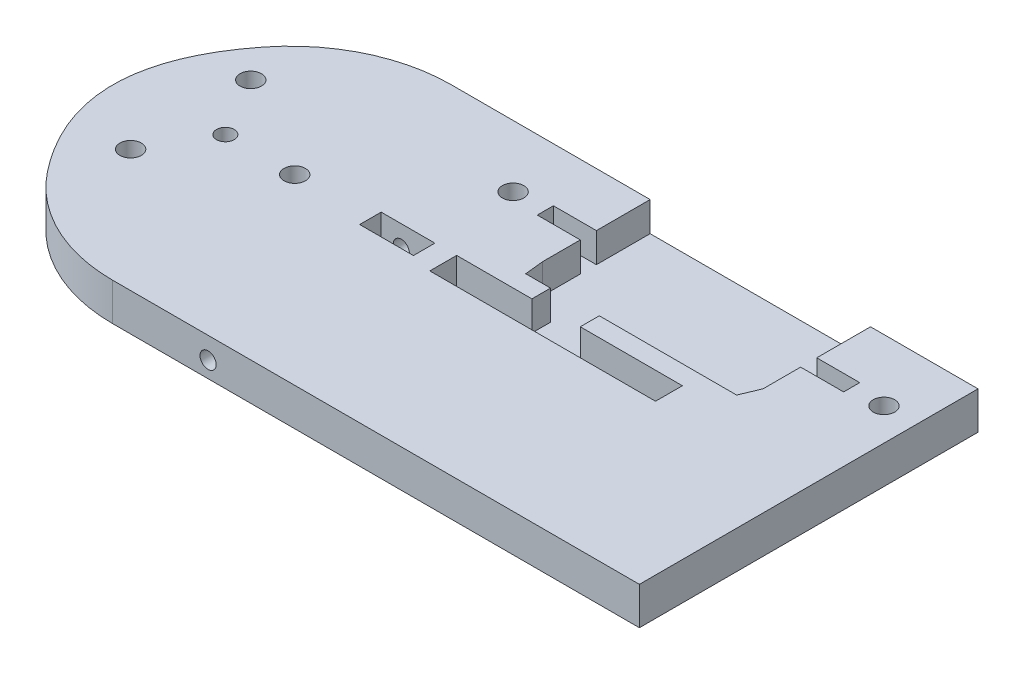
SolidWorks part; units mm, degrees
ref_plane "Plan de face" through (0, 0, 0) normal (0, 0, 1) x (1, 0, 0)
ref_plane "Plan de dessus" through (0, 0, 0) normal (0, 1, 0) x (1, 0, 0)
ref_plane "Plan de droite" through (0, 0, 0) normal (1, 0, 0) x (0, 0, -1)
sketch "Esquisse1" plane through (0, 0, 0) normal (0, 1, 0) x (1, 0, 0)
  line L0 (110, 31.5) -> (-33.3405, 31.5) construction
  line L1 (0, 0) -> (110, 0)
  line L3 (0, 63) -> (110, 63)
  line L4 (110, 0) -> (110, 63)
  spline S0 degree 2 poles (0, 63) (-38.9544, 31.5) (0, 0) knots 0 0 0 1 1 1
  dimension "D1" = 110
  dimension "D2" = 63
extrude "Boss.-Extru.1" add sketch "Esquisse1" along normal blind 7 contours S0 L1 L4 L3
sketch "Esquisse2" plane through (0, 7, 0) normal (0, 1, 0) x (1, 0, 0)
  line L0 (90, 63) -> (90, 53)
  line L1 (0, 63) -> (110, 63) construction
  line L2 (90, 53) -> (98, 53)
  line L3 (98, 53) -> (98, 50)
  line L4 (98, 50) -> (90, 50)
  line L5 (90, 50) -> (90, 43)
  line L6 (88.5483, 39.5408) -> (90, 43)
  line L7 (49, 43) -> (49, 50)
  line L8 (49, 50) -> (41, 50)
  line L9 (41, 50) -> (41, 53)
  line L10 (41, 53) -> (49, 53)
  line L11 (49, 53) -> (49, 63)
  line L12 (49, 63) -> (90, 63)
  line L13 (49, 43) -> (49.3831, 39.4665)
  line L14 (49.3831, 39.4665) -> (54, 39.4665)
  line L15 (63, 39.5408) -> (88.5483, 39.5408)
  line L16 (54, 39.4665) -> (54, 35.886)
  line L17 (54, 35.886) -> (63, 35.886)
  line L18 (63, 35.886) -> (63, 39.5408)
  dimension "D1" = 20
  dimension "D2" = 5
  dimension "D3" = 41
  dimension "D4" = 10
  dimension "D5" = 10
  dimension "D6" = 3
  dimension "D7" = 3
  dimension "D8" = 8
  dimension "D9" = 8
  dimension "D10" = 8
  dimension "D11" = 7
  dimension "D12" = 9
extrude "Enlèv. mat.-Extru.1" cut sketch "Esquisse2" against normal blind 5.5
sketch "Esquisse3" plane through (0, 7, 0) normal (0, 1, 0) x (1, 0, 0)
  line L0 (40, 36) -> (82, 36)
  line L1 (82, 36) -> (82, 31)
  line L2 (82, 31) -> (40, 31)
  line L3 (40, 31) -> (40, 36)
  line L4 (90, 63) -> (110, 63) construction
  line L5 (41, 53) -> (41, 50) construction
  dimension "D1" = 27
  dimension "D2" = 5
  dimension "D3" = 42
  dimension "D4" = 1
extrude "Enlèv. mat.-Extru.2" cut sketch "Esquisse3" against normal blind 7
sketch "Esquisse4" plane through (0, 7, 0) normal (0, 1, 0) x (1, 0, 0)
  line L0 (31.7529, 51.5) -> (111.7589, 51.5) construction
  line L1 (98, 50) -> (98, 53) construction
  line L2 (41, 53) -> (41, 50) construction
  circle A0 centre (104, 51.5) radius 2
  circle A1 centre (35, 51.5) radius 2
  dimension "D1" = 4
  dimension "D3" = 4
  dimension "D2" = 6
  dimension "D4" = 6
extrude "Enlèv. mat.-Extru.3" cut sketch "Esquisse4" against normal blind 7
sketch "Esquisse5" plane through (0, 7, 0) normal (0, 1, 0) x (1, 0, 0)
  line L0 (34, 35.9527) -> (34, 31.9527)
  line L1 (34, 31.9527) -> (26, 31.9527)
  line L2 (26, 31.9527) -> (26, 35.9527)
  line L3 (26, 35.9527) -> (34, 35.9527)
  line L4 (40, 36) -> (40, 31) construction
  dimension "D1" = 4
  dimension "D2" = 8
  dimension "D3" = 6
extrude "Enlèv. mat.-Extru.4" cut sketch "Esquisse5" against normal blind 7
chamfer "Chanfrein1" distance 2 angle 48 1 edges at (34, 7, -33.9527)
sketch "Esquisse6" plane through (0, 7, 0) normal (0, 1, 0) x (1, 0, 0)
  line L0 (26, 33.9527) -> (-18.0549, 33.9527) construction
  line L1 (26, 35.9527) -> (26, 31.9527) construction
  line L2 (11.9169, 33.9527) -> (-7.4388, 45.1277) construction
  line L3 (-7.4388, 45.1277) -> (-7.4388, 22.7777) construction
  line L4 (11.9169, 33.9527) -> (-7.4388, 22.7777) construction
  circle A0 centre (11.9169, 33.9527) radius 2
  circle A1 centre (-7.4388, 45.1277) radius 2
  circle A2 centre (-7.4388, 22.7777) radius 2
  circle A3 centre (-0.9869, 33.9527) radius 1.65
  point P12 (-0.9869, 33.9527)
  point P13 (-0.9869, 33.9527)
  dimension "D1" = 4
  dimension "D8" = 4
  dimension "D9" = 4
  dimension "D10" = 3.3
  dimension "D2" = 22.35
  dimension "D3" = 22.35
  dimension "D4" = 22.35
  dimension "D5" = 60
  dimension "D6" = 60
  dimension "D7" = 60
extrude "Enlèv. mat.-Extru.5" cut sketch "Esquisse6" against normal blind 7
sketch "Esquisse7" plane through (0, 0, -63) normal (0, 0, -1) x (-1, 0, 0)
  line L0 (0, 7) -> (-49, 7) construction
  circle A0 centre (-29.75, 3) radius 1.5
  dimension "D1" = 3
  dimension "D2" = 4
extrude "Enlèv. mat.-Extru.6" cut sketch "Esquisse7" against normal blind 67
fillet "Congé1" radius 30 2 edges at (0, 3.5, 0) (0, 3.5, -63)
